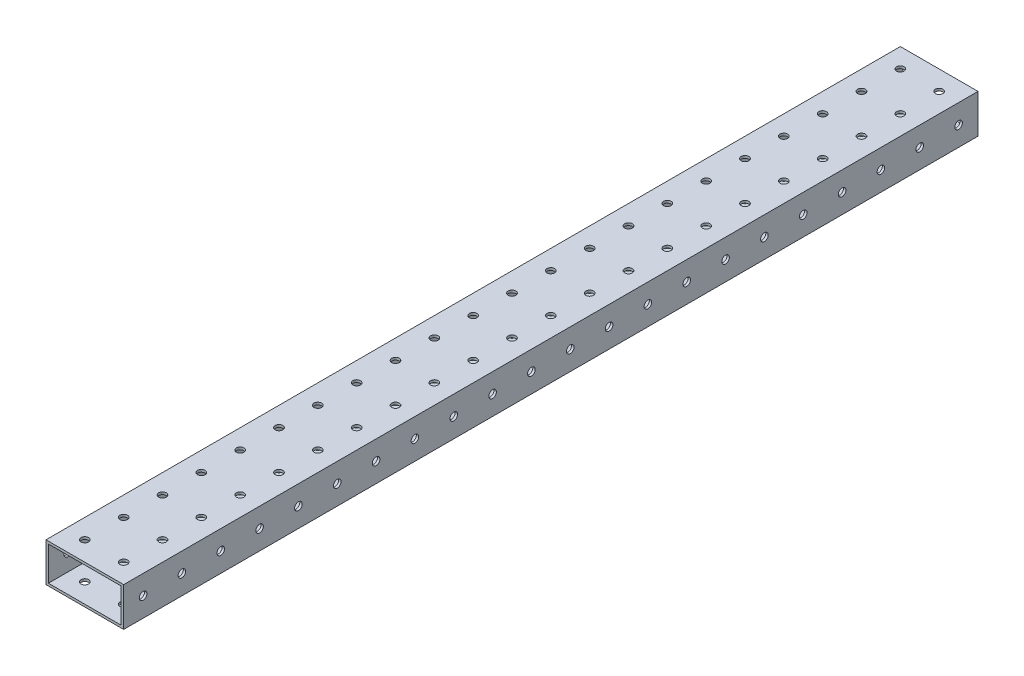
SolidWorks part; units mm, degrees
material "6061-T6 (SS)"
ref_plane "Front Plane" through (0, 0, 0) normal (0, 0, 1) x (1, 0, 0)
ref_plane "Top Plane" through (0, 0, 0) normal (0, 1, 0) x (1, 0, 0)
ref_plane "Right Plane" through (0, 0, 0) normal (1, 0, 0) x (0, 0, -1)
sketch "Sketch1" plane through (0, 0, 0) normal (0, 0, 1) x (1, 0, 0)
  line L1 (0, 0) -> (50.8, 0)
  line L2 (0, 0) -> (0, 25.4)
  line L3 (0, 25.4) -> (50.8, 25.4)
  line L4 (50.8, 0) -> (50.8, 25.4)
  dimension "D1" = 50.8
  dimension "D2" = 25.4
extrude "Boss-Extrude1" add sketch "Sketch1" along normal mid plane 558.8
shell "Shell1" thickness 1.5875
sketch "Sketch2" plane through (0, 0, 0) normal (0, -1, 0) x (1, 0, 0)
  line L0 (0, 279.4) -> (50.8, 279.4) construction
  line L1 (0, 279.4) -> (0, -279.4) construction
  circle A0 centre (12.7, 266.7) radius 2.4892
  dimension "D3" = 4.9784
  dimension "D1" = 12.7
  dimension "D2" = 12.7
extrude "Cut-Extrude1" cut sketch "Sketch2" against normal through all
pattern_linear "LPattern1" count 2 spacing 25.4 along (1, 0, 0) count 22 spacing 25.4 along (0, 0, -1) of "Cut-Extrude1"
sketch "Sketch3" plane through (0, 0, 0) normal (-1, 0, 0) x (0, 0, 1)
  line L0 (-279.4, 25.4) -> (-279.4, 0) construction
  circle A0 centre (-266.7, 12.7) radius 2.4892
  point P2 (0, 0)
  point P5 (-279.4, 12.7)
  dimension "D1" = 4.9784
  dimension "D2" = 12.7
extrude "Cut-Extrude2" cut sketch "Sketch3" against normal through all
pattern_linear "LPattern2" count 22 spacing 25.4 along (0, 0, 1) of "Cut-Extrude2"
